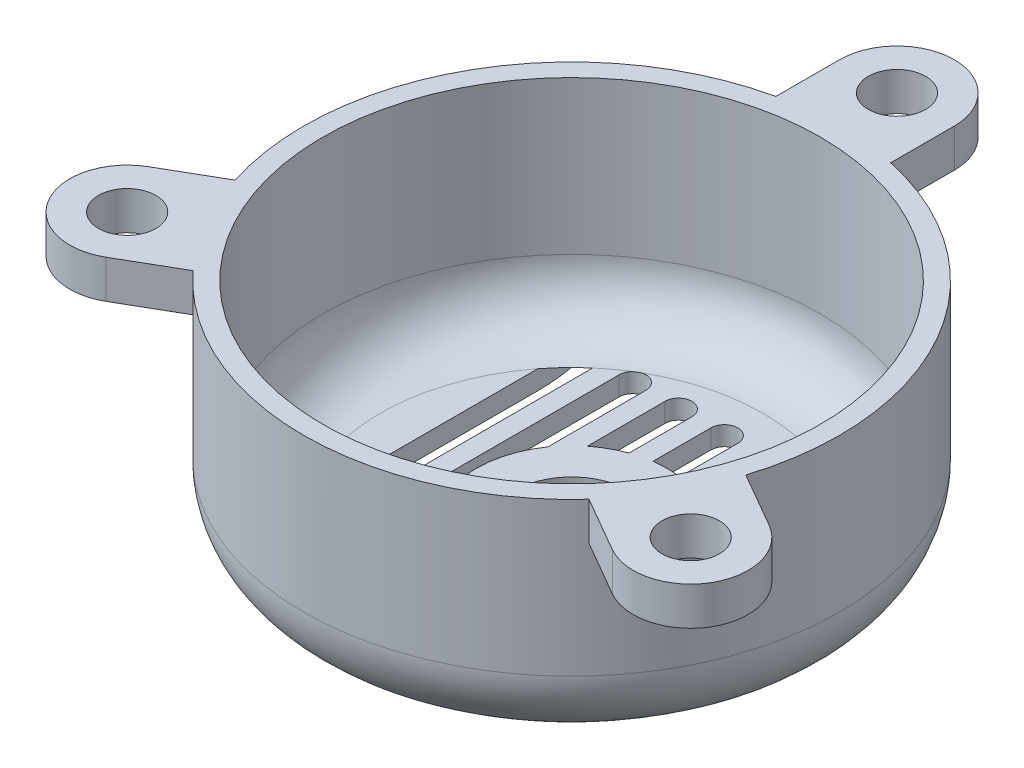
SolidWorks part; units mm, degrees
ref_plane "Front Plane" through (0, 0, 0) normal (0, 0, 1) x (1, 0, 0)
ref_plane "Top Plane" through (0, 0, 0) normal (0, 1, 0) x (1, 0, 0)
ref_plane "Right Plane" through (0, 0, 0) normal (1, 0, 0) x (0, 0, -1)
sketch "Sketch2" plane through (0, 0, 0) normal (0, 1, 0) x (1, 0, 0)
  circle A0 centre (0, 0) radius 88.9
  dimension "D1" = 177.8
extrude "Boss-Extrude1" add sketch "Sketch2" along normal blind 76.2
fillet "Fillet1" radius 25.4 1 edges at (0, 0, 88.9)
shell "Shell1" thickness 6.35
sketch "Sketch3" plane through (0, 6.35, 0) normal (0, 1, 0) x (1, 0, 0)
  line L0 (45.72, 50.6996) -> (45.72, -50.9004) construction
  line L1 (50.165, 50.6996) -> (50.165, -50.9004)
  line L2 (41.275, 50.6996) -> (41.275, -50.9004)
  line L3 (0, 0) -> (45.72, 0) construction
  line L4 (26.035, 50.6996) -> (26.035, -50.9004)
  line L5 (34.925, 50.6996) -> (34.925, -50.9004)
  line L6 (30.48, 50.6996) -> (30.48, -50.9004) construction
  line L7 (10.795, 50.6996) -> (10.795, -50.9004)
  line L8 (19.685, 50.6996) -> (19.685, -50.9004)
  line L9 (15.24, 50.6996) -> (15.24, -50.9004) construction
  line L10 (-4.445, 50.6996) -> (-4.445, -50.9004)
  line L11 (4.445, 50.6996) -> (4.445, -50.9004)
  line L12 (0, 50.6996) -> (0, -50.9004) construction
  line L13 (-19.685, 50.6996) -> (-19.685, -50.9004)
  line L14 (-10.795, 50.6996) -> (-10.795, -50.9004)
  line L15 (-15.24, 50.6996) -> (-15.24, -50.9004) construction
  line L16 (-34.925, 50.6996) -> (-34.925, -50.9004)
  line L17 (-26.035, 50.6996) -> (-26.035, -50.9004)
  line L18 (-30.48, 50.6996) -> (-30.48, -50.9004) construction
  line L19 (-50.165, 50.6996) -> (-50.165, -50.9004)
  line L20 (-41.275, 50.6996) -> (-41.275, -50.9004)
  line L21 (-45.72, 50.6996) -> (-45.72, -50.9004) construction
  line L22 (41.275, 50.6996) -> (26.035, 50.6996) construction
  arc A0 (50.165, 50.6996) -> (41.275, 50.6996) centre (45.72, 50.6996) ccw
  arc A1 (41.275, -50.9004) -> (50.165, -50.9004) centre (45.72, -50.9004) ccw
  arc A2 (34.925, 50.6996) -> (26.035, 50.6996) centre (30.48, 50.6996) ccw
  arc A3 (26.035, -50.9004) -> (34.925, -50.9004) centre (30.48, -50.9004) ccw
  arc A4 (19.685, 50.6996) -> (10.795, 50.6996) centre (15.24, 50.6996) ccw
  arc A5 (10.795, -50.9004) -> (19.685, -50.9004) centre (15.24, -50.9004) ccw
  arc A6 (4.445, 50.6996) -> (-4.445, 50.6996) centre (0, 50.6996) ccw
  arc A7 (-4.445, -50.9004) -> (4.445, -50.9004) centre (0, -50.9004) ccw
  arc A8 (-10.795, 50.6996) -> (-19.685, 50.6996) centre (-15.24, 50.6996) ccw
  arc A9 (-19.685, -50.9004) -> (-10.795, -50.9004) centre (-15.24, -50.9004) ccw
  arc A10 (-26.035, 50.6996) -> (-34.925, 50.6996) centre (-30.48, 50.6996) ccw
  arc A11 (-34.925, -50.9004) -> (-26.035, -50.9004) centre (-30.48, -50.9004) ccw
  arc A12 (-41.275, 50.6996) -> (-50.165, 50.6996) centre (-45.72, 50.6996) ccw
  arc A13 (-50.165, -50.9004) -> (-41.275, -50.9004) centre (-45.72, -50.9004) ccw
  point P2 (45.72, -0.1004)
  point P14 (30.48, -0.1004)
  point P21 (15.24, -0.1004)
  point P28 (0, -0.1004)
  point P35 (-15.24, -0.1004)
  point P42 (-30.48, -0.1004)
  point P49 (-45.72, -0.1004)
  dimension "D1" = 45.72
  dimension "D2" = 8.89
  dimension "D3" = 101.6
  dimension "D5" = 15.24
  dimension "D4" = 7
extrude "Cut-Extrude1" cut sketch "Sketch3" against normal up to next contours L2 A1 L1 A0 | L5 A3 L4 A2 | L8 A5 L7 A4 | L11 A7 L10 A6 | L14 A9 L13 A8 | L17 A11 L16 A10 | L20 A13 L19 A12
sketch "Sketch6" plane through (0, 6.35, 0) normal (0, 1, 0) x (1, 0, 0)
  circle A0 centre (0, 0) radius 31.75
  dimension "D1" = 63.5
extrude "Boss-Extrude2" add sketch "Sketch6" against normal blind 19.05
sketch "Sketch7" plane through (0, -12.7, 0) normal (0, -1, 0) x (1, 0, 0)
  circle A0 centre (0, 0) radius 19.05
  dimension "D1" = 38.1
extrude "Cut-Extrude2" cut sketch "Sketch7" against normal up to next
sketch "Sketch9" plane through (0, 76.2, 0) normal (0, 1, 0) x (1, 0, 0)
  line L0 (-19.05, 107.95) -> (-19.05, 86.8349)
  line L1 (19.05, 107.95) -> (19.05, 86.8349)
  circle A0 centre (0, 0) radius 107.95 construction
  circle A1 centre (0, 107.95) radius 9.525
  arc A2 (19.05, 107.95) -> (-19.05, 107.95) centre (0, 107.95) ccw
  circle A3 centre (0, 0) radius 88.9 construction
  arc A4 (19.05, 86.8349) -> (-19.05, 86.8349) centre (0, 0) ccw
  point P9 (18.9757, 84.8687)
  point P12 (-18.9757, 84.8687)
  dimension "D1" = 215.9
  dimension "D2" = 19.05
  dimension "D3" = 38.1
  dimension "D4" = 19.05
extrude "Boss-Extrude3" add sketch "Sketch9" against normal blind 12.7
pattern_circular "CirPattern1" count 3 over 360 about axis through (0, 0, 0) along (0, 1, 0) of "Boss-Extrude3"
